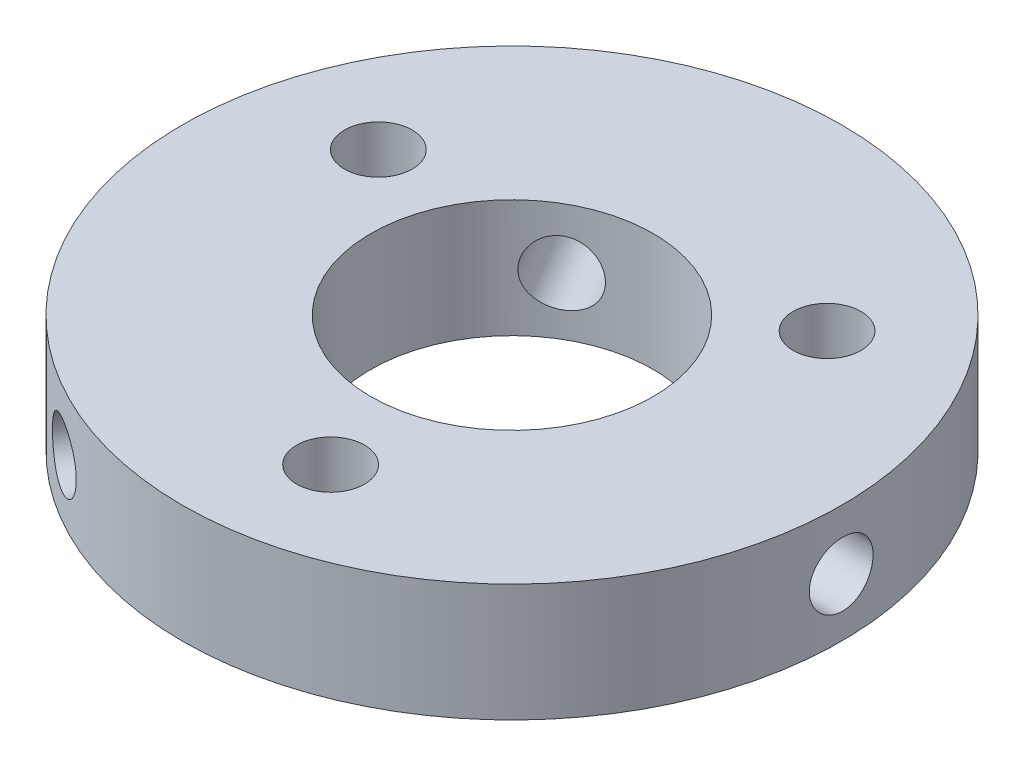
SolidWorks part; units mm, degrees
ref_plane "Front Plane" through (0, 0, 0) normal (0, 0, 1) x (1, 0, 0)
ref_plane "Top Plane" through (0, 0, 0) normal (0, 1, 0) x (1, 0, 0)
ref_plane "Right Plane" through (0, 0, 0) normal (1, 0, 0) x (0, 0, -1)
sketch "Sketch1" plane through (0, 0, 0) normal (0, 1, 0) x (1, 0, 0)
  circle A0 centre (0, 0) radius 17.78
  dimension "D1" = 35.56
extrude "Boss-Extrude1" add sketch "Sketch1" along normal blind 6.35
hole_wizard "CBORE for #6 Socket Head Cap Screw1" [suppressed] positions "Sketch3" profile "Sketch4" counterbore size "#6" standard "ANSI Inch"
sketch "Sketch3" plane through (0, 6.35, 0) normal (0, 1, 0) x (1, 0, 0)
  line L3 (0, 0) -> (8.5312, -8.5312)
  point P0 (8.5312, -8.5312)
sketch "Sketch4" plane through (8.5312, 6.35, 8.5312) normal (1, 0, 0) x (0, 0, 1)
  line L0 (0, 0) -> (0, 6.35)
  line L1 (0, 6.35) -> (1.8288, 6.35)
  line L3 (1.8288, 6.35) -> (1.8288, 3.5052)
  line L4 (1.8288, 3.5052) -> (3.5725, 3.5052)
  line L5 (3.5725, 3.5052) -> (3.5725, 0)
  line L7 (3.5725, 0) -> (0, 0)
  line L11 (0, -6.35) -> (0, 107.95) construction
  dimension "Thru Hole Dia." = 3.6576
  dimension "Thru Hole Depth" = 6.35
  dimension "C'Bore Dia." = 7.145
  dimension "C'Bore Depth" = 3.5052
pattern_circular "CirPattern1" [suppressed] count 3 over 360
sketch "Sketch9" plane through (0, 6.35, 0) normal (0, 1, 0) x (1, 0, 0)
  line L0 (0, 0) -> (9.2423, 7.7552)
  circle A0 centre (9.2423, 7.7552) radius 1.4122
ref_plane "Plane1" [suppressed] through (0, 3.175, 0) normal (0, 1, 0) x (1, 0, 0)
sketch "Sketch11" [suppressed] plane through (0, 3.175, 0) normal (0, 1, 0) x (1, 0, 0)
  line L0 (0, 0) -> (-7.135, -12.0105)
  circle A0 centre (0, 0) radius 13.97 construction
ref_plane "Plane2" [suppressed] through (-7.135, 3.175, 12.0105) normal (-0.5107, 0, 0.8597) x (0.8597, 0, 0.5107)
hole_wizard "Tap Drill for #8-32 Tap2" positions "3DSketch3" profile "Sketch15" hole size "#8-32" standard "ANSI Inch"
sketch3d "3DSketch3"
  point P0 (-8.8359, 3.1056, 15.429)
sketch "Sketch15" plane through (-8.8359, 3.1056, 15.429) normal (0, 1, 0) x (0.8678, 0, 0.497)
  line L0 (0, 0) -> (0, 14.1493)
  line L1 (0, 14.1493) -> (1.7272, 12.7)
  line L2 (1.7272, 12.7) -> (1.7272, 0)
  line L5 (1.7272, 0) -> (0, 0)
  line L10 (0, 14.1493) -> (-1.7272, 12.7) construction
  line L11 (0, -6.35) -> (0, 107.95) construction
  dimension "Hole Dia." = 3.4544
  dimension "Hole Depth" = 12.7
  dimension "Drill Angle" = 100
pattern_circular "CirPattern3" count 3 every 120 about axis through (0, 6.35, 0) along (0, -1, 0) of "Tap Drill for #8-32 Tap2"
sketch "Sketch16" plane through (0, 6.35, 0) normal (0, 1, 0) x (1, 0, 0)
  circle A0 centre (0, 0) radius 7.62
extrude "Cut-Extrude2" cut sketch "Sketch16" against normal up to next contours A0
sketch "Sketch18" plane through (0, 0, 0) normal (0, -1, 0) x (1, 0, 0)
  line L0 (0, 0) -> (9.2423, -7.7552)
hole_wizard "CBORE for #6 Socket Head Cap Screw4" positions "3DSketch6" profile "Sketch20" counterbore size "#6" standard "ANSI Inch" end condition through all
sketch3d "3DSketch6"
  point P0 (9.2423, 0, -7.7552)
sketch "Sketch20" plane through (9.2423, 0, -7.7552) normal (1, 0, 0) x (0, 0, -1)
  line L0 (0, 0) -> (0, 6.35)
  line L1 (0, 6.35) -> (1.8288, 6.35)
  line L3 (1.8288, 6.35) -> (1.8288, 3.5052)
  line L4 (1.8288, 3.5052) -> (3.5725, 3.5052)
  line L5 (3.5725, 3.5052) -> (3.5725, 0)
  line L7 (3.5725, 0) -> (0, 0)
  line L11 (0, -6.35) -> (0, 107.95) construction
  dimension "Thru Hole Dia." = 3.6576
  dimension "Thru Hole Depth" = 6.35
  dimension "C'Bore Dia." = 7.145
  dimension "C'Bore Depth" = 3.5052
pattern_circular "CirPattern4" count 3 every 120 about axis through (0, 0, 0) along (0, 1, 0) of "CBORE for #6 Socket Head Cap Screw4"
